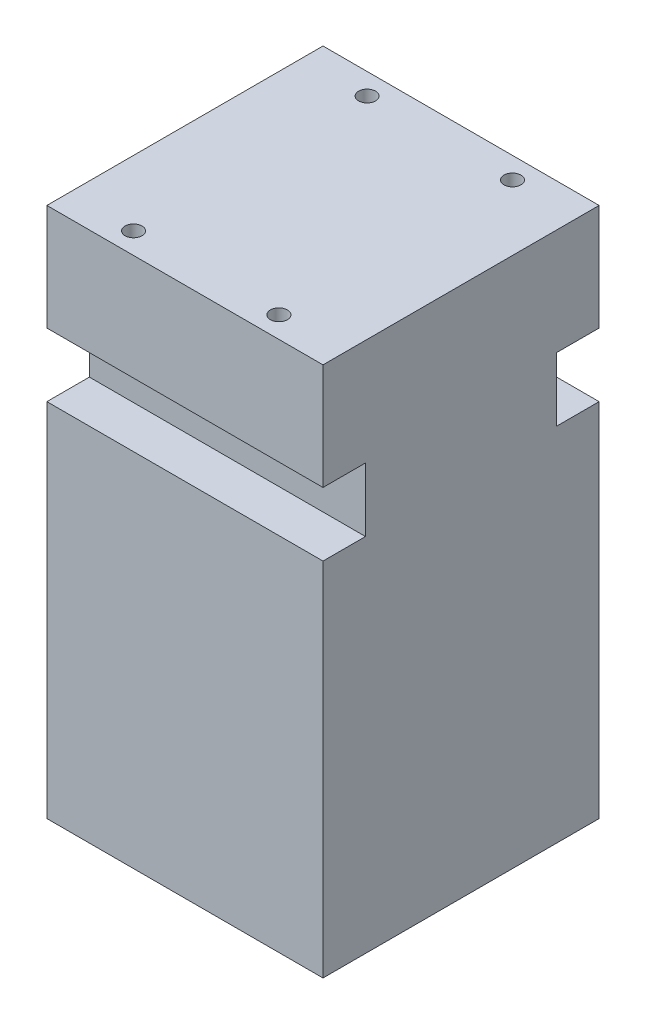
SolidWorks part; units mm, degrees
ref_plane "Front Plane" through (0, 0, 0) normal (0, 0, 1) x (1, 0, 0)
ref_plane "Top Plane" through (0, 0, 0) normal (0, 1, 0) x (1, 0, 0)
ref_plane "Right Plane" through (0, 0, 0) normal (1, 0, 0) x (0, 0, -1)
sketch "Sketch2" plane through (0, 0, 0) normal (0, 1, 0) x (1, 0, 0)
  line L1 (0, 0) -> (260, 0)
  line L2 (0, 0) -> (0, 260)
  line L3 (0, 260) -> (260, 260)
  line L4 (260, 0) -> (260, 260)
  dimension "D1" = 260
  dimension "D2" = 260
extrude "Boss-Extrude1" add sketch "Sketch2" along normal blind 500
sketch "Sketch4" plane through (260, 0, 0) normal (1, 0, 0) x (0, 0, -1)
  line L0 (0, 500) -> (0, 400)
  line L1 (0, 500) -> (0, 0) construction
  line L2 (0, 400) -> (40, 400)
  line L3 (40, 400) -> (40, 340)
  line L4 (40, 340) -> (0, 340)
  line L5 (0, 400) -> (0, 340)
  point P5 (40, 370)
  line M6 (0, 500) -> (0, 0)
  dimension "D1" = 30
  dimension "D2" = 40
  dimension "D3" = 100
extrude "Cut-Extrude1" cut sketch "Sketch4" against normal through all both and the other way through all contours L4 L3 L2 M6
ref_plane "Plane1" through (0, 0, -130) normal (0, 0, -1) x (-1, 0, 0)
sketch "Sketch5" plane through (0, 500, 0) normal (0, 1, 0) x (1, 0, 0)
  line L0 (0, 260) -> (123.1123, 260)
  line L1 (260, 260) -> (0, 260) construction
  line L2 (123.1123, 260) -> (61.5561, 260)
  line L3 (61.5561, 260) -> (61.5561, 0)
  line L4 (0, 0) -> (260, 0) construction
  line L5 (61.5561, 0) -> (61.5561, 130)
  line L6 (61.5561, 130) -> (61.5561, 20.048)
  circle A0 centre (61.5561, 20.048) radius 8
  dimension "D1" = 16
extrude "Cut-Extrude2" cut sketch "Sketch5" against normal up to next contours L6 A0 L5 | L5 A0 L6
ref_plane "Plane2" through (130, 0, 0) normal (-1, 0, 0) x (0, 0, 1)
mirror "Mirror1" about plane through (130, 0, 0) normal (-1, 0, 0) of "Cut-Extrude2"
mirror "Mirror2" about plane through (0, 0, -130) normal (0, 0, -1) of "Cut-Extrude1", "Mirror1", "Cut-Extrude2"
